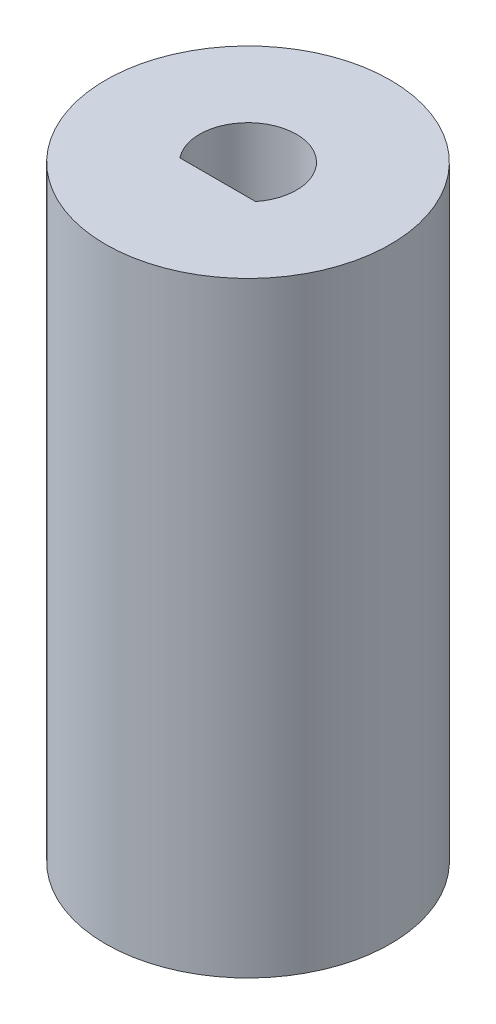
SolidWorks part; units mm, degrees
material "Custom Plastic"
ref_plane "Front Plane" through (0, 0, 0) normal (0, 0, 1) x (1, 0, 0)
ref_plane "Top Plane" through (0, 0, 0) normal (0, 1, 0) x (1, 0, 0)
ref_plane "Right Plane" through (0, 0, 0) normal (1, 0, 0) x (0, 0, -1)
sketch "Sketch1" plane through (0, 0, 0) normal (0, 0, 1) x (1, 0, 0)
  line L0 (0, 0) -> (0, 12.2143) construction
  line L1 (-1.2, 0) -> (-1.2, 20)
  line L2 (-1.2, 20) -> (-4.7, 20)
  line L3 (-4.7, 20) -> (-4.7, 0)
  line L4 (-4.7, 0) -> (-1.2, 0)
  line L5 (-1.2, 10.8595) -> (-0.8488, 10.8595)
  line L6 (-0.8488, 10.8595) -> (-0.8488, 20)
  line L7 (-1.2, 20) -> (1.2, 20) construction
  line L8 (-0.8488, 20) -> (-1.2, 20)
  dimension "D1" = 2.4
  dimension "D2" = 3.5
  dimension "D3" = 20
revolve "Revolve1" add sketch "Sketch1" angle 360 about L0
sketch "Sketch3" plane through (0, 20, 0) normal (0, 1, 0) x (1, 0, 0)
  line L0 (-1.249, -1) -> (1.249, -1)
  line L1 (-2.0017, 1.43) -> (2.0017, 1.43)
  line L2 (-2.0017, 1.43) -> (-2.0017, -1.43) construction
  line L3 (-2.0017, -1.43) -> (2.0017, -1.43)
  line L4 (2.0017, 1.43) -> (2.0017, -1.43) construction
  line L5 (-1.2, -0.9) -> (1.2, -0.9)
  line L6 (-1.2, -0.9) -> (1.2, -0.9)
  arc A0 (-2.0017, 1.43) -> (-2.0017, -1.43) centre (0, 0) ccw
  arc A1 (2.0017, 1.43) -> (-2.0017, 1.43) centre (0, 0) ccw construction
  arc A2 (2.0017, -1.43) -> (2.0017, 1.43) centre (0, 0) ccw
  arc A3 (-2.0017, -1.43) -> (2.0017, -1.43) centre (0, 0) ccw construction
  arc A4 (1.249, -1) -> (-1.249, -1) centre (0, 0) ccw
  arc A5 (1.2, -0.9) -> (-1.2, -0.9) centre (0, 0) ccw
  arc A6 (1.2, -0.9) -> (-1.2, -0.9) centre (0, 0) ccw
  circle M17 centre (0, 0) radius 0.8488
  dimension "D2" = 4.92
  dimension "D1" = 2.86
  dimension "D3" = 0
  dimension "D4" = 0.1
extrude "Cut-Extrude1" cut sketch "Sketch3" against normal blind 8 contours L6 A6 L1 M17 | L1 A6 | A6 L1 A4 | A6 L6 L1 A4 L0 | M17
